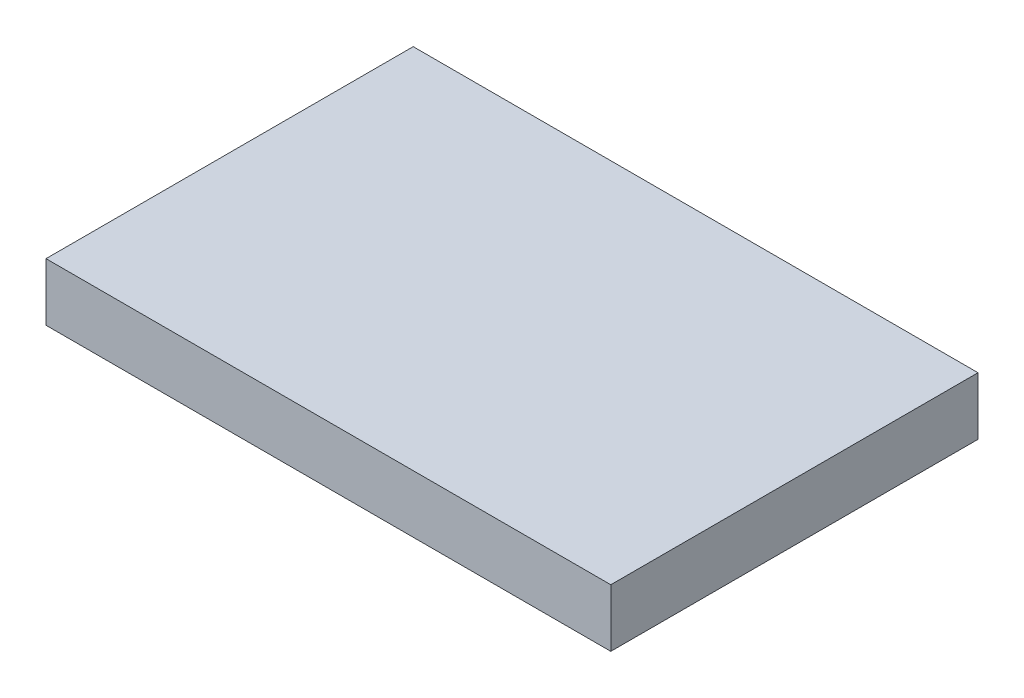
SolidWorks part; units mm, degrees
material "ABS"
ref_plane "Front Plane" through (0, 0, 0) normal (0, 0, 1) x (1, 0, 0)
ref_plane "Top Plane" through (0, 0, 0) normal (0, 1, 0) x (1, 0, 0)
ref_plane "Right Plane" through (0, 0, 0) normal (1, 0, 0) x (0, 0, -1)
sketch "Sketch1" plane through (0, 0, 0) normal (0, 1, 0) x (1, 0, 0)
  line L1 (0, 0) -> (82.042, 0)
  line L2 (0, 0) -> (0, -53.34)
  line L3 (0, -53.34) -> (82.042, -53.34)
  line L4 (82.042, 0) -> (82.042, -53.34)
  dimension "D1" = 82.042
  dimension "D2" = 53.34
extrude "Boss-Extrude1" add sketch "Sketch1" along normal blind 8.382
